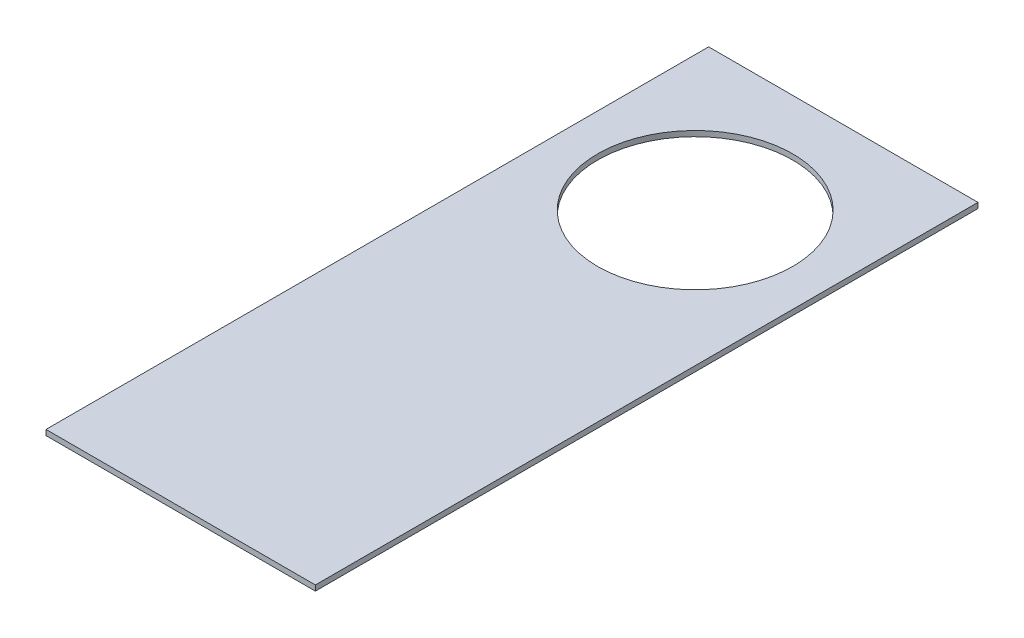
SolidWorks part; units mm, degrees
ref_plane "Front Plane" through (0, 0, 0) normal (0, 0, 1) x (1, 0, 0)
ref_plane "Top Plane" through (0, 0, 0) normal (0, 1, 0) x (1, 0, 0)
ref_plane "Right Plane" through (0, 0, 0) normal (1, 0, 0) x (0, 0, -1)
sketch "Sketch1" plane through (0, 0, 0) normal (0, 1, 0) x (1, 0, 0)
  line L1 (0, 0) -> (158.75, 0)
  line L2 (0, 0) -> (0, 390.525)
  line L3 (0, 390.525) -> (158.75, 390.525)
  line L4 (158.75, 0) -> (158.75, 390.525)
  dimension "D1" = 158.75
  dimension "D2" = 390.525
extrude "Boss-Extrude1" add sketch "Sketch1" along normal blind 3.175
sketch "Sketch4" plane through (0, 3.175, 0) normal (0, 1, 0) x (1, 0, 0)
  line L1 (19.375, 363.2125) -> (139.375, 363.2125) construction
  line L2 (19.375, 363.2125) -> (19.375, 243.2125) construction
  line L3 (19.375, 243.2125) -> (139.375, 243.2125) construction
  line L4 (139.375, 363.2125) -> (139.375, 243.2125) construction
  line L5 (158.75, 390.525) -> (0, 390.525) construction
  line L7 (26.1938, 356.3937) -> (132.5562, 356.3937) construction
  line L8 (26.1938, 356.3937) -> (26.1938, 250.0312) construction
  line L9 (26.1938, 250.0312) -> (132.5563, 250.0312) construction
  line L10 (132.5562, 356.3937) -> (132.5563, 250.0312) construction
  circle A5 centre (79.375, 303.2125) radius 57.5
  point P7 (79.375, 363.2125)
  point P8 (79.375, 248.225)
  point P9 (79.375, 356.3938)
  point P10 (132.5562, 303.2125)
  point P11 (139.375, 303.2125)
  point P13 (0, 0)
  point P15 (0, 0)
  point P20 (79.375, 390.525)
  dimension "D3" = 303.2125
  dimension "D8" = 115
  dimension "D1" = 120
  dimension "D2" = 120
  dimension "D4" = 106.3625
extrude "Cut-Extrude1" cut sketch "Sketch4" against normal through all
